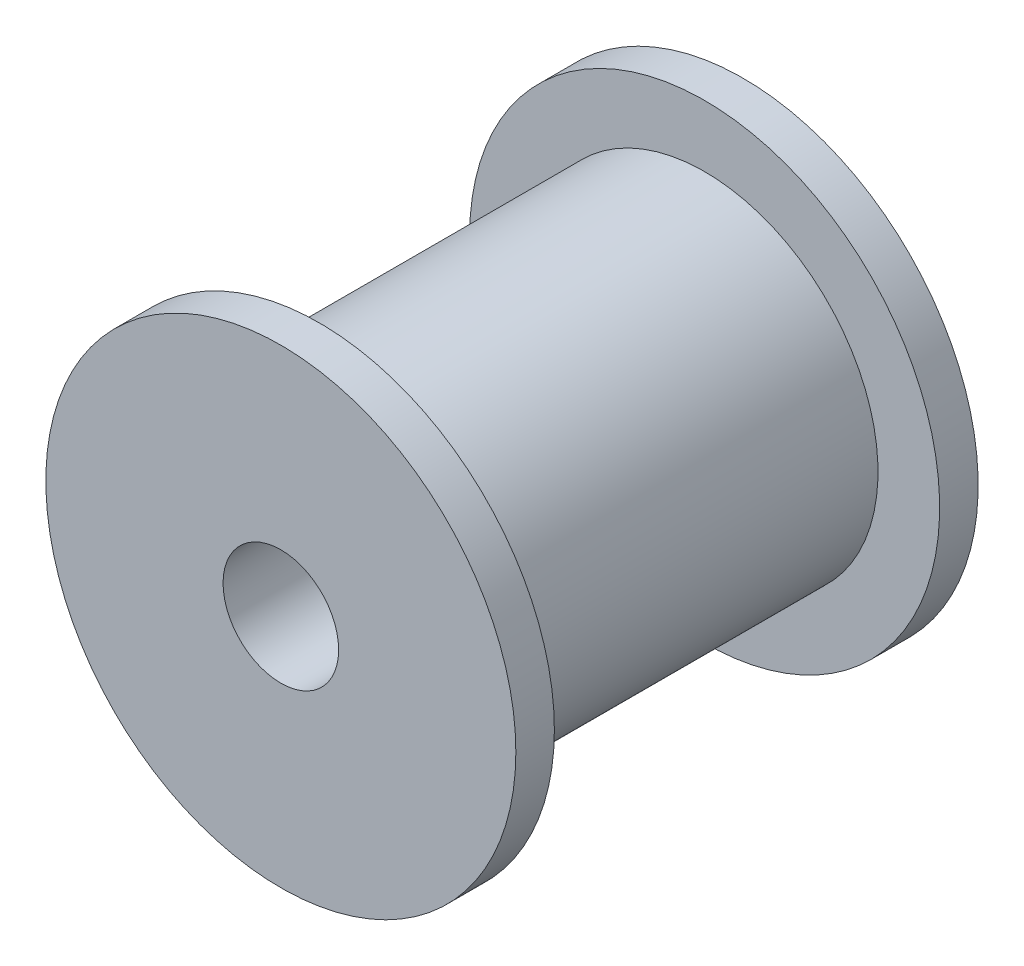
SolidWorks part; units mm, degrees
ref_plane "Plan de face" through (0, 0, 0) normal (0, 0, 1) x (1, 0, 0)
ref_plane "Plan de dessus" through (0, 0, 0) normal (0, 1, 0) x (1, 0, 0)
ref_plane "Plan de droite" through (0, 0, 0) normal (1, 0, 0) x (0, 0, -1)
sketch "Esquisse1" plane through (0, 0, 0) normal (0, 0, 1) x (1, 0, 0)
  circle A0 centre (0, 0) radius 1.5
  circle A1 centre (0, 0) radius 6.1
extrude "Boss.-Extru.1" add sketch "Esquisse1" along normal blind 1 contours A1 A0
sketch "Esquisse2" plane through (0, 0, 0) normal (0, 0, -1) x (-1, 0, 0)
  circle A0 centre (0, 0) radius 1.5
  circle A1 centre (0, 0) radius 4.5
extrude "Boss.-Extru.2" add sketch "Esquisse2" along normal blind 10
sketch "Esquisse3" plane through (0, 0, -10) normal (0, 0, -1) x (-1, 0, 0)
  circle A0 centre (0, 0) radius 1.5
  circle A1 centre (0, 0) radius 6.1
extrude "Boss.-Extru.3" add sketch "Esquisse3" along normal blind 1
